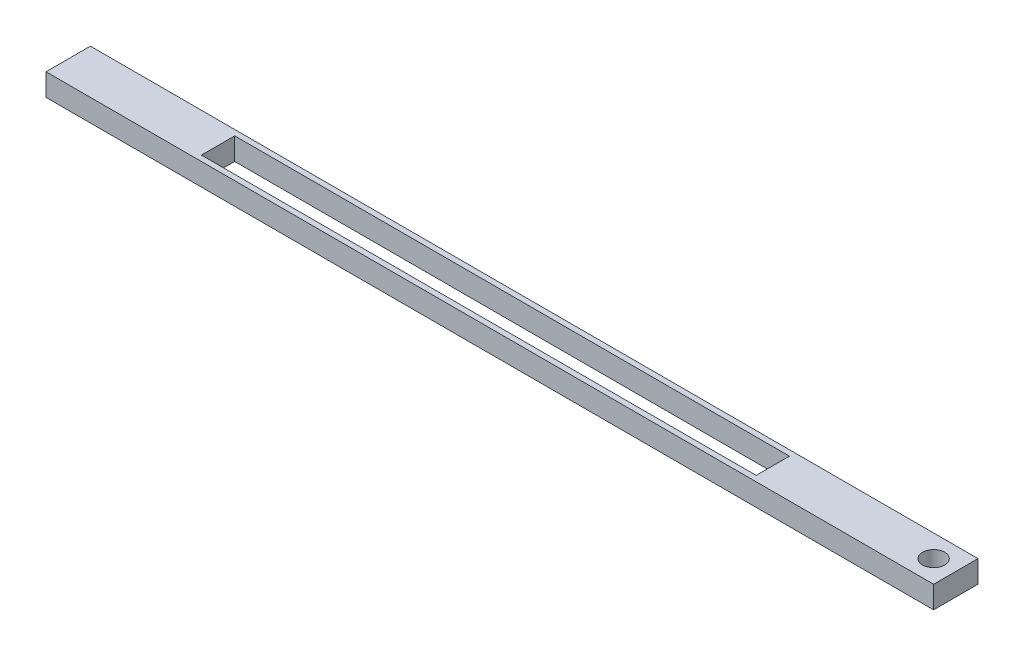
SolidWorks part; units mm, degrees
ref_plane "Спереди" through (0, 0, 0) normal (0, 0, 1) x (1, 0, 0)
ref_plane "Сверху" through (0, 0, 0) normal (0, 1, 0) x (1, 0, 0)
ref_plane "Справа" through (0, 0, 0) normal (1, 0, 0) x (0, 0, -1)
sketch "Эскиз1" plane through (0, 0, 0) normal (0, 0, 1) x (1, 0, 0)
  line L1 (-200, -5) -> (200, -5)
  line L2 (-200, -5) -> (-200, 5)
  line L3 (-200, 5) -> (200, 5)
  line L4 (200, -5) -> (200, 5)
  line L5 (-200, -5) -> (200, 5) construction
  line L6 (-200, 5) -> (200, -5) construction
  point P0 (0, 0)
  dimension "D1" = 10
  dimension "D2" = 400
extrude "Бобышка-Вытянуть1" add sketch "Эскиз1" along normal blind 20
sketch "Эскиз2" plane through (0, 5, 0) normal (0, 1, 0) x (1, 0, 0)
  line L1 (-132.4637, -17.5) -> (117.5363, -17.5)
  line L2 (-132.4637, -17.5) -> (-132.4637, -2.5)
  line L3 (-132.4637, -2.5) -> (117.5363, -2.5)
  line L4 (117.5363, -17.5) -> (117.5363, -2.5)
  line L5 (-132.4637, -17.5) -> (117.5363, -2.5) construction
  line L6 (-132.4637, -2.5) -> (117.5363, -17.5) construction
  line L7 (200, 0) -> (-200, 0) construction
  point P0 (-7.4637, -10)
  point P8 (0, 0)
  point P9 (0, 0)
  point P10 (0, 0)
  point P11 (0, 0)
  dimension "D1" = 10
  dimension "D2" = 7.4637
  dimension "D3" = 250
  dimension "D4" = 15
extrude "Вырез-Вытянуть1" cut sketch "Эскиз2" against normal blind 20
sketch "Эскиз4" plane through (0, 5, 0) normal (0, 1, 0) x (1, 0, 0)
  line L0 (200, -20) -> (200, 0) construction
  line L1 (200, -20) -> (-200, -20) construction
  circle A0 centre (190, -10) radius 5
  point P4 (0, 0)
  point P7 (0, 0)
  dimension "D1" = 10
  dimension "D2" = 10
  dimension "D3" = 10
extrude "Вырез-Вытянуть3" cut sketch "Эскиз4" against normal blind 20
